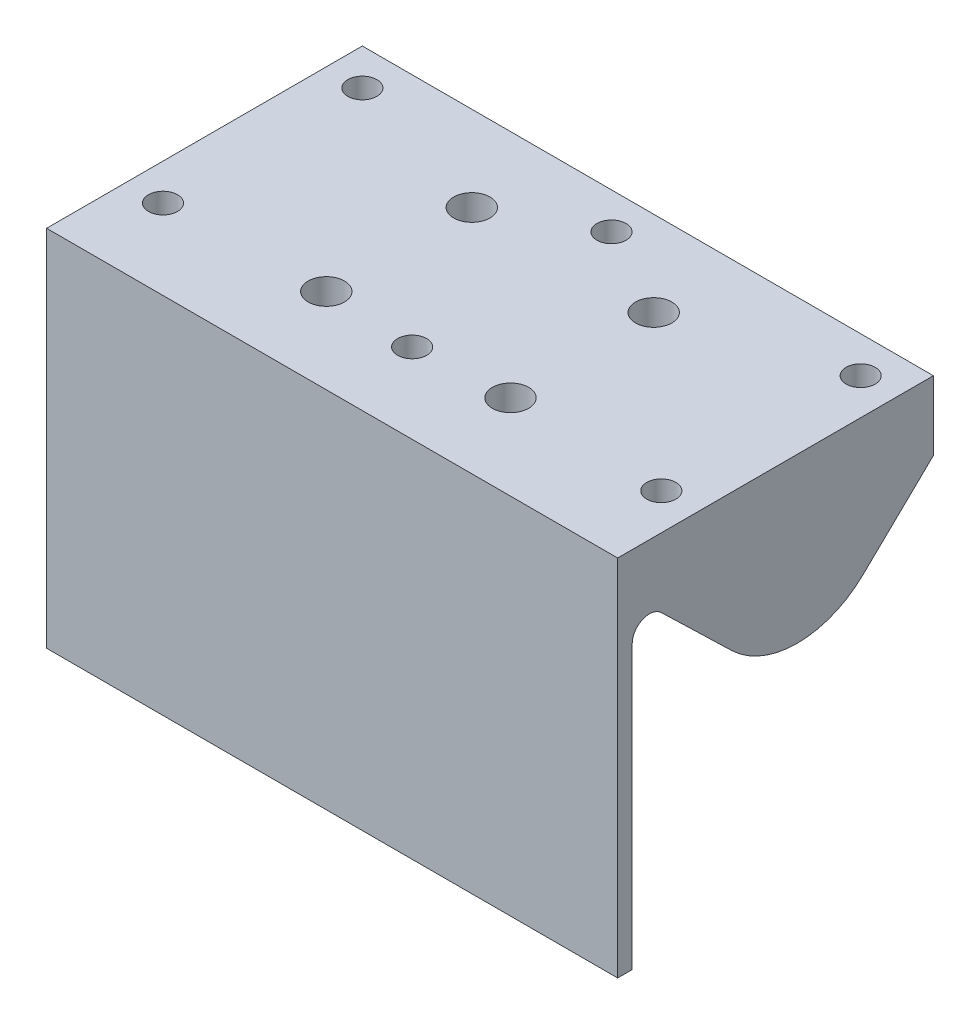
SolidWorks part; units mm, degrees
ref_plane "Front Plane" through (0, 0, 0) normal (0, 0, 1) x (1, 0, 0)
ref_plane "Top Plane" through (0, 0, 0) normal (0, 1, 0) x (1, 0, 0)
ref_plane "Right Plane" through (0, 0, 0) normal (1, 0, 0) x (0, 0, -1)
sketch "Sketch1" plane through (0, 0, 0) normal (0, 1, 0) x (1, 0, 0)
  line L0 (-35.25, 14.7) -> (35.25, -14.7) construction
  line L1 (-35.25, 14.7) -> (35.25, 14.7) construction
  line L2 (-35.25, 14.7) -> (-35.25, -14.7) construction
  line L3 (-35.25, -14.7) -> (35.25, -14.7) construction
  line L4 (35.25, 14.7) -> (35.25, -14.7) construction
  line L5 (-39.25, 0) -> (-35.25, 0) construction
  line L6 (-39.25, 18.7) -> (39.25, 18.7)
  line L7 (-39.25, 18.7) -> (-39.25, -18.7)
  line L8 (-39.25, -18.7) -> (39.25, -18.7)
  line L9 (39.25, 18.7) -> (39.25, -18.7)
  line L10 (35.25, 0) -> (39.25, 0) construction
  line L11 (0, 18.7) -> (0, 14.7) construction
  dimension "D1" = 70.5
  dimension "D2" = 29.4
  dimension "D4" = 4
extrude "Boss-Extrude1" add sketch "Sketch1" along normal blind 9.5
sketch "Sketch6" plane through (0, 9.5, 0) normal (0, 1, 0) x (1, 0, 0)
  line L0 (-34.25, 13.7) -> (0, 13.7) construction
  line L1 (0, 13.7) -> (34.25, 13.7) construction
  line L2 (34.25, 13.7) -> (34.25, -13.7) construction
  line L3 (34.25, -13.7) -> (0, -13.7) construction
  line L4 (0, -13.7) -> (-34.25, -13.7) construction
  line L5 (-34.25, -13.7) -> (-34.25, 13.7) construction
  line L6 (-34.25, 13.7) -> (34.25, -13.7) construction
  line L7 (39.25, 18.7) -> (-39.25, 18.7) construction
  line L8 (0, 13.7) -> (0, 18.7) construction
  line L9 (-34.25, 0) -> (-39.25, 0) construction
  line L10 (-39.25, 18.7) -> (-39.25, -18.7) construction
  circle A0 centre (-34.25, 13.7) radius 2
  circle A1 centre (0, 13.7) radius 2
  circle A2 centre (34.25, 13.7) radius 2
  circle A3 centre (34.25, -13.7) radius 2
  circle A4 centre (0, -13.7) radius 2
  circle A5 centre (-34.25, -13.7) radius 2
  dimension "D1" = 4
  dimension "D2" = 5
extrude "Cut-Extrude1" cut sketch "Sketch6" against normal blind 6.5
sketch "Sketch7" plane through (-39.25, 0, 0) normal (-1, 0, 0) x (0, 0, 1)
  line L1 (-18.7, 0) -> (-9.0374, -9.3448)
  line L2 (-9.0374, -9.3448) -> (9.0374, -9.3448) construction
  line L3 (9.0374, -9.3448) -> (18.7, 0)
  line L6 (-18.7, 0) -> (18.7, 0) construction
  line L7 (-18.7, 0) -> (18.7, 0)
  arc A1 (-9.0374, -9.3448) -> (9.0374, -9.3448) centre (0, 0) ccw
  dimension "D3" = 13
extrude "Boss-Extrude2" add sketch "Sketch7" against normal blind 4
mirror "Mirror1" about plane through (0, 0, 0) normal (1, 0, 0) of "Boss-Extrude2"
sketch "Sketch9" plane through (0, 0, -18.7) normal (0, 0, -1) x (-1, 0, 0)
  line L1 (18.25, 7.5) -> (31.25, 7.5)
  line L2 (18.25, 7.5) -> (18.25, 2)
  line L3 (18.25, 2) -> (31.25, 2)
  line L4 (31.25, 7.5) -> (31.25, 2)
  line L5 (39.25, 9.5) -> (39.25, 0) construction
  line L8 (-39.25, 9.5) -> (39.25, 9.5) construction
  line L9 (24.75, 2) -> (24.75, 0) construction
  line L10 (-35.25, 0) -> (35.25, 0) construction
  line L11 (24.75, 7.5) -> (24.75, 9.5) construction
  line L12 (-18.25, 2) -> (0, 0) construction
  line L13 (-31.25, 7.5) -> (-18.25, 7.5)
  line L14 (-31.25, 7.5) -> (-31.25, 2)
  line L15 (-31.25, 2) -> (-18.25, 2)
  line L16 (-18.25, 7.5) -> (-18.25, 2)
  line L17 (0, 0) -> (18.25, 2) construction
  dimension "D1" = 13
  dimension "D2" = 8
  dimension "D3" = 2
extrude "Cut-Extrude3" cut sketch "Sketch9" against normal through all
sketch "Sketch11" plane through (-39.25, 0, 0) normal (-1, 0, 0) x (0, 0, 1)
  line L7 (18.7, 9.5) -> (24.7, 9.5)
  line L9 (24.7, 9.5) -> (24.7, -40.5)
  line L10 (24.7, -40.5) -> (22.7, -40.5)
  line L11 (22.7, -40.5) -> (22.7, 3.5)
  line L13 (18.7, 9.5) -> (18.7, 0) construction
  line L14 (18.7, 7.5) -> (18.7, 9.5)
  line L15 (18.7, 7.5) -> (12.7, 7.5) construction
  arc A1 (18.7, 7.5) -> (22.7, 3.5) centre (18.7, 3.5) cw
  dimension "D1" = 4
  dimension "D2" = 2
  dimension "D3" = 50
extrude "Boss-Extrude3" add sketch "Sketch11" against normal up to surface (78.5 mm away) contours L7 L9 L10 L11 A1 L14 up to face at (39.25, -0.5575, 0)
sketch "Sketch12" plane through (39.25, 0, 0) normal (1, 0, 0) x (0, 0, -1)
  line L1 (-9.0374, -9.3448) -> (-18.7, 0) construction
  line L2 (-18.7, 7.5) -> (-18.7, 0) construction
  line L3 (-18.7, 7.5) -> (-18.7, 0)
  line L4 (-22.7, 3.5) -> (-22.7, -1.6962)
  line L5 (-22.7, 3.5) -> (-22.7, -40.5) construction
  arc A0 (-18.7, 0) -> (-22.7, -1.6962) centre (-20.3404, -1.6962) ccw
  arc A3 (-18.7, 7.5) -> (-22.7, 3.5) centre (-18.7, 3.5) ccw construction
  arc A4 (-18.7, 7.5) -> (-22.7, 3.5) centre (-18.7, 3.5) ccw
extrude "Boss-Extrude4" add sketch "Sketch12" against normal up to surface (4 mm away) contours A0 L4 A4 L3 up to face at (35.25, -5.5862, 0)
sketch "Sketch13" plane through (-39.25, 0, 0) normal (-1, 0, 0) x (0, 0, 1)
  line L2 (22.7, -1.6962) -> (22.7, 3.5)
  line L3 (18.7, 7.5) -> (18.7, 0)
  line L4 (22.7, -1.6962) -> (22.7, 3.5)
  line L5 (18.7, 7.5) -> (18.7, 0)
  arc A2 (22.7, -1.6962) -> (18.7, 0) centre (20.3404, -1.6962) ccw
  arc A3 (22.7, 3.5) -> (18.7, 7.5) centre (18.7, 3.5) ccw
  arc A4 (22.7, -1.6962) -> (18.7, 0) centre (20.3404, -1.6962) ccw
  arc A5 (22.7, 3.5) -> (18.7, 7.5) centre (18.7, 3.5) ccw
  dimension "D1" = 0
extrude "Boss-Extrude5" add sketch "Sketch13" against normal up to surface (4 mm away) up to face at (-35.25, -5.5862, 0)
sketch "Sketch15" plane through (0, 9.5, 0) normal (0, 1, 0) x (1, 0, 0)
  circle A0 centre (-12.5, 7) radius 2.5
  circle A1 centre (-12.5, -13) radius 2.5
  circle A2 centre (12.8167, -13) radius 2.5
  circle A3 centre (12.5, 7) radius 2.5
  dimension "D1" = 5
extrude "Cut-Extrude4" cut sketch "Sketch15" against normal blind 15
sketch "Sketch16" plane through (0, 0, 0) normal (0, -1, 0) x (1, 0, 0)
  circle A0 centre (-12.5, 13) radius 4
  circle A1 centre (12.8167, 13) radius 4
  circle A2 centre (12.5, -7) radius 4
  circle A3 centre (-12.5, -7) radius 4
  dimension "D1" = 8
extrude "Cut-Extrude5" cut sketch "Sketch16" against normal blind 3
